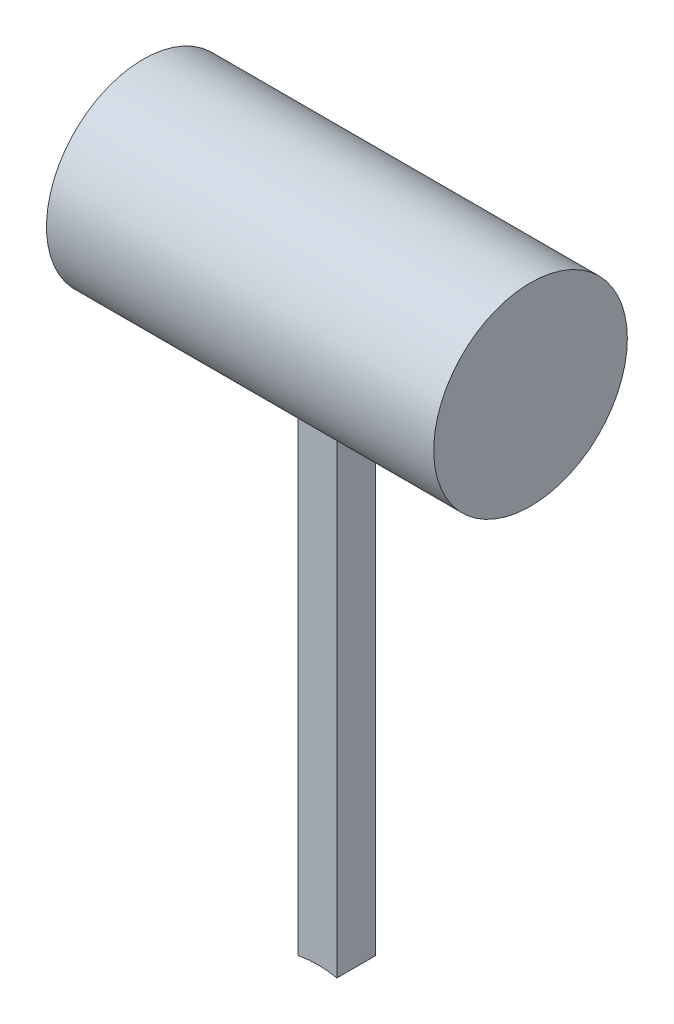
SolidWorks part; units mm, degrees
ref_plane "Front Plane" through (0, 0, 0) normal (0, 0, 1) x (1, 0, 0)
ref_plane "Top Plane" through (0, 0, 0) normal (0, 1, 0) x (1, 0, 0)
ref_plane "Right Plane" through (0, 0, 0) normal (1, 0, 0) x (0, 0, -1)
sketch "Sketch1" plane through (0, 0, 0) normal (1, 0, 0) x (0, 0, -1)
  circle A0 centre (0, 0) radius 5
  dimension "D1" = 10
extrude "Boss-Extrude1" add sketch "Sketch1" along normal mid plane 20
sketch "Sketch2" plane through (0, 0, 0) normal (0, 0, 1) x (1, 0, 0)
  line L1 (-1, 0) -> (1, 0)
  line L2 (-1, 0) -> (-1, -35)
  line L3 (-1, -35) -> (1, -35)
  line L4 (1, 0) -> (1, -35)
  circle A0 centre (0, -35) radius 5
  point P4 (0, 0)
  dimension "D3" = 10
  dimension "D1" = 2
  dimension "D2" = 35
extrude "Boss-Extrude2" add sketch "Sketch2" along normal mid plane 2 contours A0 L4 L1 L2
